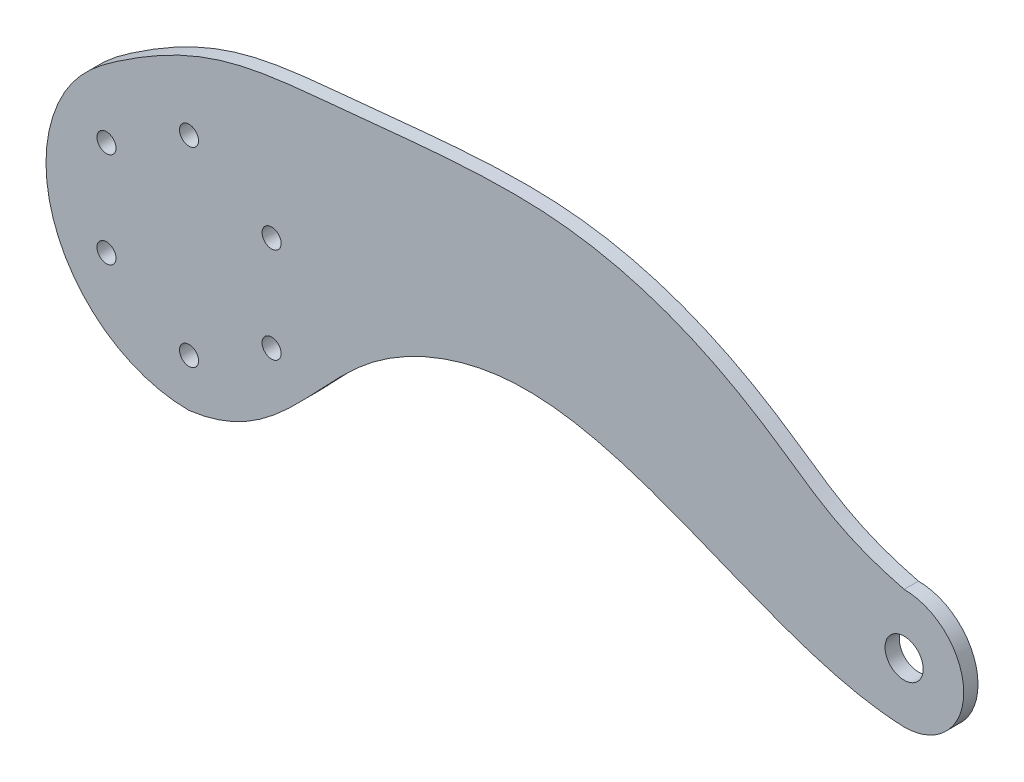
SolidWorks part; units mm, degrees
material "6063-T6"
ref_plane "Front Plane" through (0, 0, 0) normal (0, 0, 1) x (1, 0, 0)
ref_plane "Top Plane" through (0, 0, 0) normal (0, 1, 0) x (1, 0, 0)
ref_plane "Right Plane" through (0, 0, 0) normal (1, 0, 0) x (0, 0, -1)
sketch "Sketch1" plane through (0, 0, 0) normal (0, 0, 1) x (1, 0, 0)
  line L0 (150, 0) -> (0, 0) construction
  line L3 (0, 0) -> (-30, 0) construction
  line L4 (0, 0) -> (0, -30) construction
  arc A8 (0, 30) -> (0, -30) centre (0, 0) ccw
  circle A9 centre (0, 0) radius 20
  circle A18 centre (0, 20) radius 2
  arc A27 (150, -12.5) -> (150, 12.5) centre (150, 0) ccw
  circle A28 centre (150, 0) radius 4
  circle A29 centre (17.3205, 10) radius 2
  circle A30 centre (17.3205, -10) radius 2
  circle A31 centre (0, -20) radius 2
  circle A32 centre (-17.3205, -10) radius 2
  circle A33 centre (-17.3205, 10) radius 2
  spline S0 degree 2 poles (150, -12.5) (154.8811, -13.0472) (159.4285, -8.207) knots 0.955766 0.955766 0.955766 1 1 1
  spline S1 degree 3 poles (0, -30) (17.9368, -27.7459) (30.1702, -2.352) (85.2159, 19.612) (122.1994, -11.5342) (150, -12.5) knots 0 0 0 0 0.288189 0.47594 1 1 1 1
  spline S2 degree 3 poles (-26.0635, 14.8558) (-22.9952, 20.2389) (2.3733, 39.108) (20.1598, 39.1077) (86.7416, 46.9998) (125.8129, 25.8301) (135.8827, 16.0755) (150, 12.5) knots 0 0 0 0 0.056044 0.324797 0.474988 0.725167 0.945335 0.945335 0.945335 0.945335
  spline S3 degree 2 poles (158.705, 8.9707) (159.0865, 8.6177) (159.4285, 8.207) knots 0.994494 0.994494 0.994494 1 1 1
  point P36 (0, 0)
  dimension "D2" = 4
  dimension "D4" = 40
  dimension "D6" = 30
  dimension "D7" = 8
  dimension "D8" = 6
  dimension "D5" = 25
  dimension "D11" = 150
extrude "Boss-Extrude3" add sketch "Sketch1" along normal blind 3
